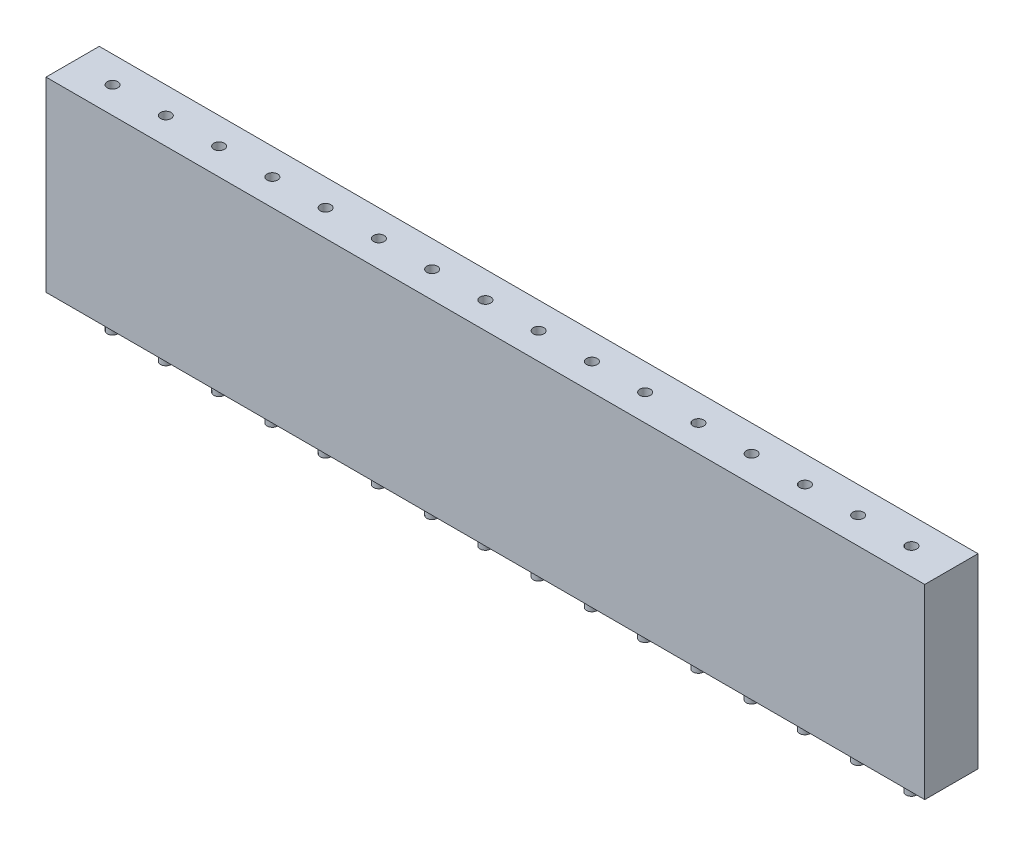
SolidWorks part; units mm, degrees
ref_plane "Front Plane" through (0, 0, 0) normal (0, 0, 1) x (1, 0, 0)
ref_plane "Top Plane" through (0, 0, 0) normal (0, 1, 0) x (1, 0, 0)
ref_plane "Right Plane" through (0, 0, 0) normal (1, 0, 0) x (0, 0, -1)
sketch "Sketch1" plane through (0, 0, 0) normal (0, 1, 0) x (1, 0, 0)
  line L7 (-20.955, 1.27) -> (20.955, 1.27)
  line L8 (-20.955, 1.27) -> (-20.955, -1.27)
  line L9 (-20.955, -1.27) -> (20.955, -1.27)
  line L10 (20.955, 1.27) -> (20.955, -1.27)
  line L11 (-20.955, 1.27) -> (20.955, -1.27) construction
  line L12 (-20.955, -1.27) -> (20.955, 1.27) construction
  dimension "D1" = 2.54
  dimension "D2" = 41.91
extrude "Extrude1" add sketch "Sketch1" along normal blind 8.89
sketch "Sketch2" plane through (0, 0, 0) normal (0, 1, 0) x (1, 0, 0)
  line L0 (20.955, -1.27) -> (20.955, 1.27) construction
  circle A0 centre (19.05, 0) radius 0.254
  circle A1 centre (16.51, 0) radius 0.254
  circle A2 centre (13.97, 0) radius 0.254
  circle A3 centre (11.43, 0) radius 0.254
  circle A4 centre (8.89, 0) radius 0.254
  circle A5 centre (6.35, 0) radius 0.254
  circle A6 centre (3.81, 0) radius 0.254
  circle A7 centre (1.27, 0) radius 0.254
  circle A8 centre (-1.27, 0) radius 0.254
  circle A9 centre (-3.81, 0) radius 0.254
  circle A10 centre (-6.35, 0) radius 0.254
  circle A11 centre (-8.89, 0) radius 0.254
  circle A12 centre (-11.43, 0) radius 0.254
  circle A13 centre (-13.97, 0) radius 0.254
  circle A14 centre (-16.51, 0) radius 0.254
  circle A15 centre (-19.05, 0) radius 0.254
  dimension "D1" = 0.508
  dimension "D2" = 1.905
extrude "Extrude2" add sketch "Sketch2" against normal blind 1.27
sketch "Sketch3" plane through (0, 8.89, 0) normal (0, 1, 0) x (1, 0, 0)
  circle A1 centre (6.35, 0) radius 0.254
  circle A2 centre (6.35, 0) radius 0.254
  circle A3 centre (8.89, 0) radius 0.254
  circle A4 centre (8.89, 0) radius 0.254
  circle A5 centre (11.43, 0) radius 0.254
  circle A6 centre (11.43, 0) radius 0.254
  circle A7 centre (13.97, 0) radius 0.254
  circle A8 centre (13.97, 0) radius 0.254
  circle A9 centre (16.51, 0) radius 0.254
  circle A10 centre (16.51, 0) radius 0.254
  circle A11 centre (19.05, 0) radius 0.254
  circle A12 centre (19.05, 0) radius 0.254
  circle A13 centre (-13.97, 0) radius 0.254
  circle A14 centre (-13.97, 0) radius 0.254
  circle A15 centre (-11.43, 0) radius 0.254
  circle A16 centre (-11.43, 0) radius 0.254
  circle A17 centre (-8.89, 0) radius 0.254
  circle A18 centre (-8.89, 0) radius 0.254
  circle A19 centre (-6.35, 0) radius 0.254
  circle A20 centre (-6.35, 0) radius 0.254
  circle A21 centre (-3.81, 0) radius 0.254
  circle A22 centre (-3.81, 0) radius 0.254
  circle A23 centre (-1.27, 0) radius 0.254
  circle A24 centre (-1.27, 0) radius 0.254
  circle A25 centre (1.27, 0) radius 0.254
  circle A26 centre (1.27, 0) radius 0.254
  circle A27 centre (3.81, 0) radius 0.254
  circle A28 centre (3.81, 0) radius 0.254
  circle A29 centre (-19.05, 0) radius 0.254
  circle A30 centre (-19.05, 0) radius 0.254
  circle A31 centre (-16.51, 0) radius 0.254
  circle A32 centre (-16.51, 0) radius 0.254
  dimension "D1" = 0
  dimension "D2" = 0
  dimension "D3" = 0
  dimension "D4" = 0
  dimension "D5" = 0
  dimension "D6" = 0
  dimension "D7" = 0
  dimension "D8" = 0
  dimension "D9" = 0
  dimension "D10" = 0
  dimension "D11" = 0
  dimension "D12" = 0
  dimension "D13" = 0
  dimension "D14" = 0
  dimension "D15" = 0
  dimension "D16" = 0
extrude "Extrude3" cut sketch "Sketch3" against normal blind 2.54
